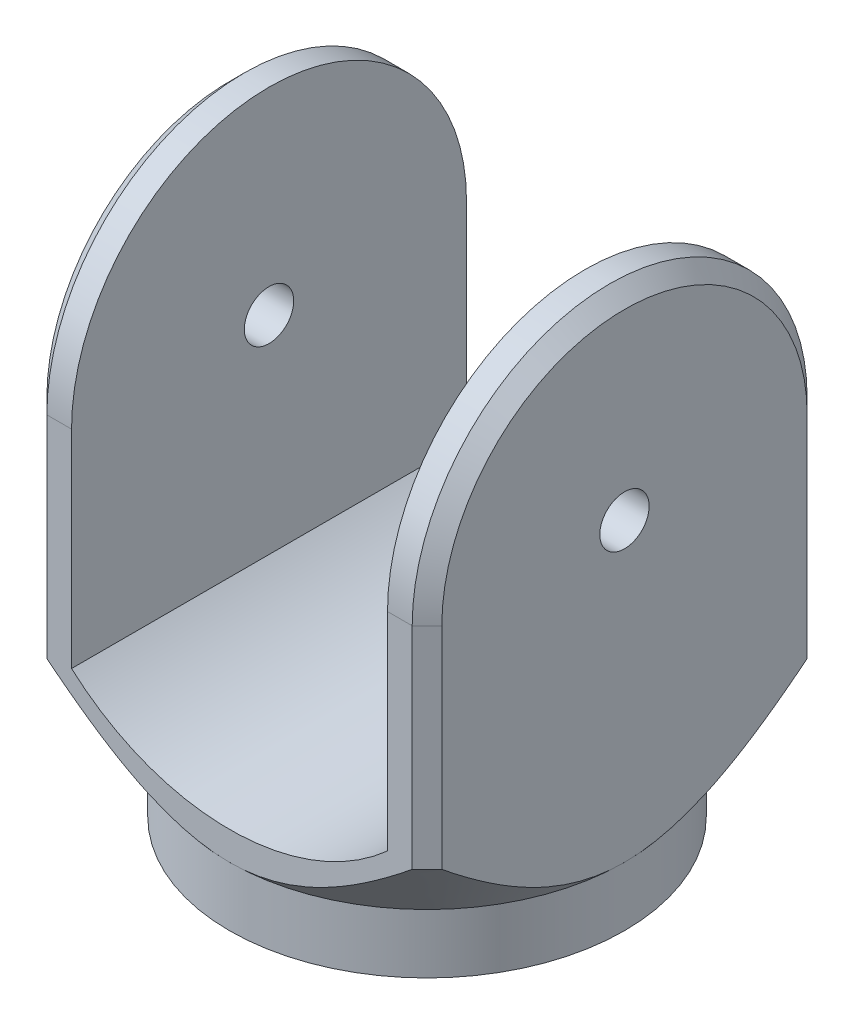
SolidWorks part; units mm, degrees
ref_plane "Front Plane" through (0, 0, 0) normal (0, 0, 1) x (1, 0, 0)
ref_plane "Top Plane" through (0, 0, 0) normal (0, 1, 0) x (1, 0, 0)
ref_plane "Right Plane" through (0, 0, 0) normal (1, 0, 0) x (0, 0, -1)
sketch "Sketch1" plane through (0, 0, 0) normal (1, 0, 0) x (0, 0, -1)
  line L0 (-100, 0) -> (-100, -180)
  line L1 (-100, -180) -> (100, -180)
  line L2 (100, -180) -> (100, 0)
  arc A0 (100, 0) -> (-100, 0) centre (0, 0) ccw
  circle A1 centre (0, 0) radius 12.5
  dimension "D1" = 100
  dimension "D3" = 25
  dimension "D2" = 180
extrude "Boss-Extrude1" add sketch "Sketch1" along normal mid plane 200
sketch "Sketch2" plane through (0, 0, 0) normal (1, 0, 0) x (0, 0, -1)
  line L0 (0, 100) -> (0, -180) construction
  line L1 (-100, -180) -> (100, -180) construction
  line L2 (100, -180) -> (100, -150)
  line L3 (100, -180) -> (100, 0) construction
  line L4 (100, -150) -> (150, -90.4123)
  line L5 (150, -90.4123) -> (150, -180)
  line L6 (150, -180) -> (100, -180)
  arc A0 (100, 0) -> (-100, 0) centre (0, 0) ccw construction
  dimension "D1" = 40
  dimension "D2" = 30
  dimension "D3" = 50
revolve "Cut-Revolve1" cut sketch "Sketch2" angle 360 about L0
sketch "Sketch3" plane through (0, 0, 0) normal (1, 0, 0) x (0, 0, -1)
  line L0 (-100, 0) -> (-100, -105)
  line L1 (-100, 0) -> (-100, -100.6359) construction
  line L2 (-100, -105) -> (100, -105)
  line L4 (100, -100.6359) -> (100, 0) construction
  line L5 (100, -105) -> (100, 0)
  line L6 (100, -150) -> (100, -100.6359) construction
  arc A0 (100, 0) -> (-100, 0) centre (0, 0) ccw
  dimension "D1" = 105
extrude "Cut-Extrude1" cut sketch "Sketch3" against normal mid plane 160
chamfer "Chamfer2" distance 7.5 angle 45 6 edges at (100, -50.318, -100) (100, -50.318, 100) (100, 100, 0) (-100, -50.318, -100) (-100, -50.318, 100) (-100, 100, 0)
sketch "Sketch4" plane through (0, 0, 100) normal (0, 0, 1) x (1, 0, 0)
  line L1 (-80, -105) -> (80, -105) construction
  line L2 (-80, -105) -> (80, -105)
  arc A0 (-80, -105) -> (80, -105) centre (0, -15.5573) ccw
  point P1 (0, -13.8526)
  dimension "D1" = 120
extrude "Cut-Extrude2" cut sketch "Sketch4" against normal through all both
